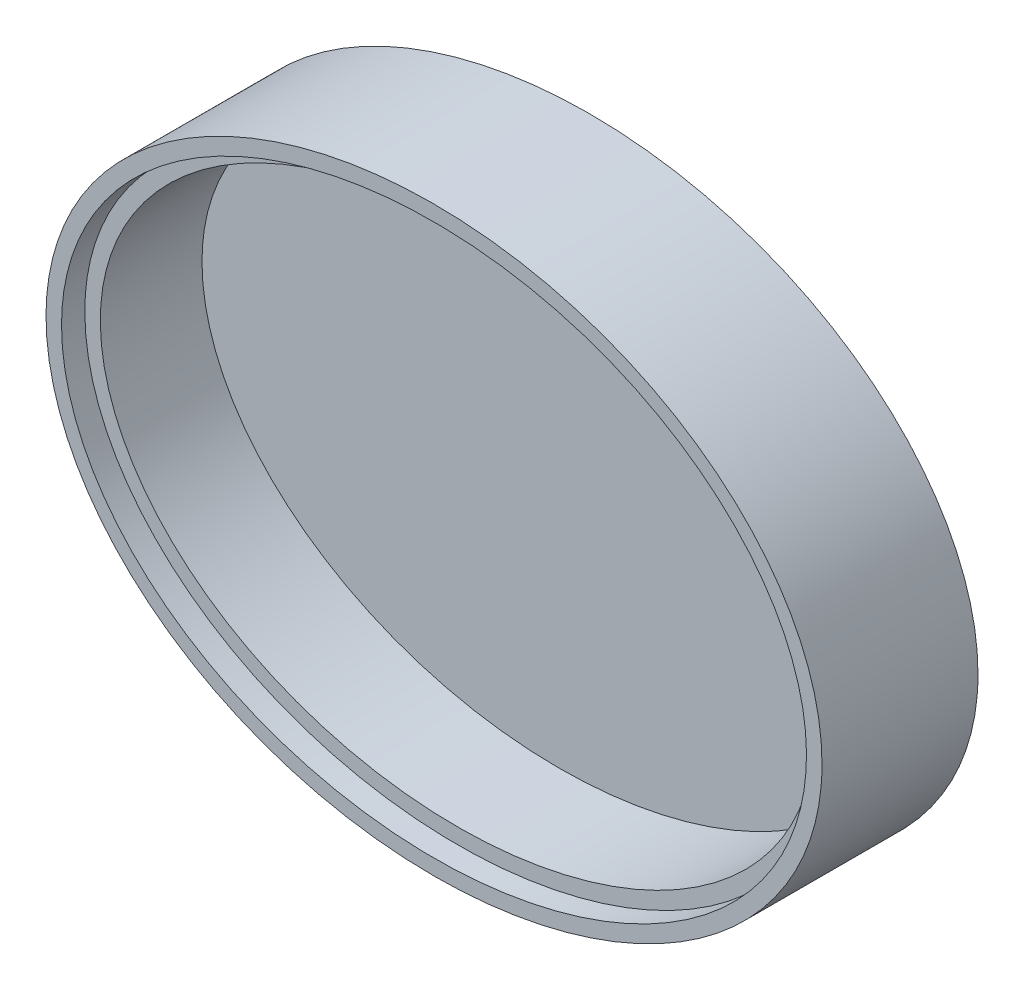
SolidWorks part; units mm, degrees
ref_plane "Front Plane" through (0, 0, 0) normal (0, 0, 1) x (1, 0, 0)
ref_plane "Top Plane" through (0, 0, 0) normal (0, 1, 0) x (1, 0, 0)
ref_plane "Right Plane" through (0, 0, 0) normal (1, 0, 0) x (0, 0, -1)
sketch "Sketch1" plane through (0, 0, 0) normal (0, 0, 1) x (1, 0, 0)
  line L0 (0, 0) -> (69.797, 0) construction
  line L1 (0, 0) -> (-64.7011, 0) construction
  ellipse E0 centre (0, 0) end of major axis (50, 0) minor radius 37.5
  dimension "D1" = 75
  dimension "D2" = 100
extrude "Boss-Extrude1" add sketch "Sketch1" along normal blind 20.1 contours E0
shell "Shell1" thickness 4
sketch "Sketch2" plane through (0, 0, 20.1) normal (0, 0, 1) x (1, 0, 0)
  ellipse E0 centre (0, 0) end of major axis (-48, 0) minor radius 35.5
extrude "Cut-Extrude1" cut sketch "Sketch2" against normal blind 3
